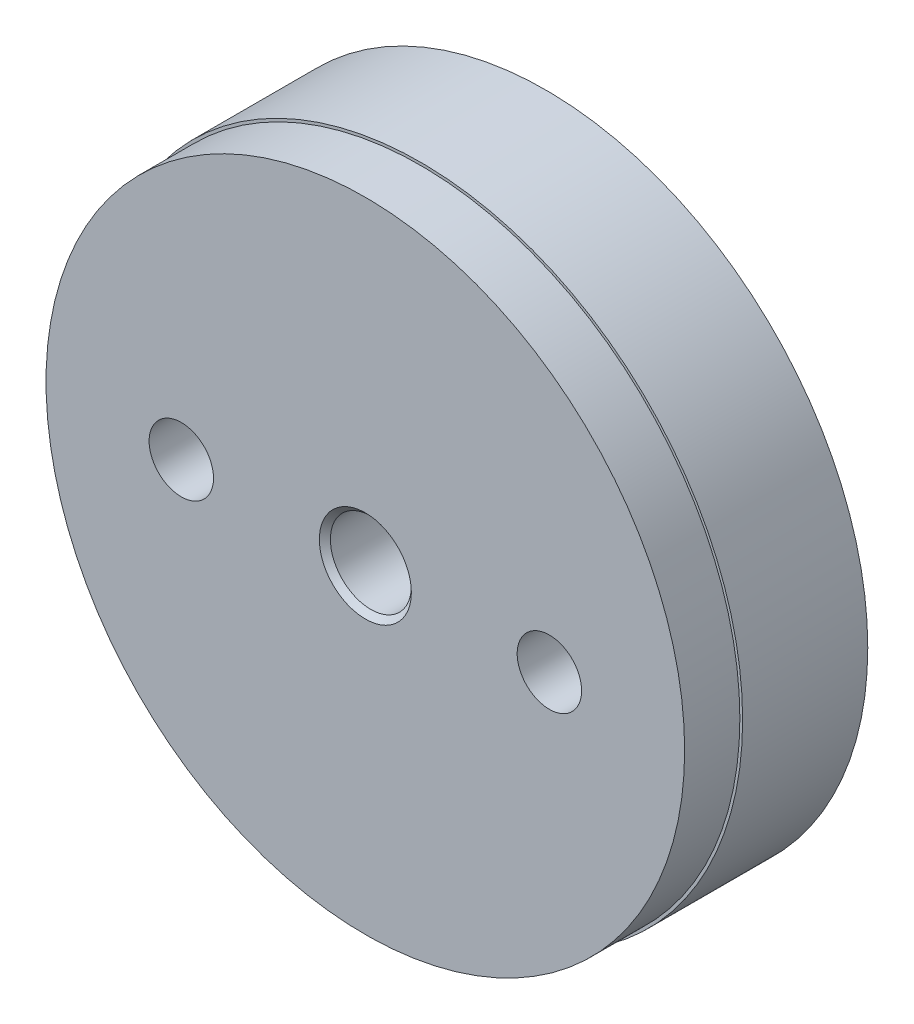
SolidWorks part; units mm, degrees
material "1.0553 (S355J0)"
ref_plane "XY Plane" through (0, 0, 0) normal (0, 0, 1) x (1, 0, 0)
ref_plane "XZ Plane" through (0, 0, 0) normal (0, 1, 0) x (1, 0, 0)
ref_plane "YZ Plane" through (0, 0, 0) normal (1, 0, 0) x (0, 0, -1)
sketch "Sketch1" plane through (0, 0, 0) normal (0, 0, 1) x (1, 0, 0)
  circle A0 centre (0, 0) radius 87.5
  dimension "D1" = 175
extrude "Boss-Extrude1" add sketch "Sketch1" along normal blind 49
sketch "Sketch2" plane through (0, 0, 49) normal (0, 0, 1) x (1, 0, 0)
  circle A0 centre (0, 0) radius 87.5 construction
  circle A1 centre (0, 0) radius 87.5
  circle A2 centre (0, 0) radius 86.75
  point P5 (0, 0)
  point P6 (0, 0)
  dimension "D1" = 173.5
extrude "Cut-Extrude1" cut sketch "Sketch2" against normal blind 15 contours A2 A1
hole_wizard "M20 Tapped Hole1" positions "Sketch3" profile "Sketch4" tap size "M20" standard "ISO" end condition through all
sketch "Sketch3" plane through (0, 0, 49) normal (0, 0, 1) x (1, 0, 0)
  line L0 (-50, 0) -> (50, 0) construction
  point P0 (-50, 0)
  point P2 (50, 0)
  dimension "D1" = 100
sketch "Sketch4" plane through (-50, 0, 49) normal (1, 0, 0) x (0, -1, 0)
  line L0 (0, 0) -> (0, 49)
  line L1 (0, 49) -> (8.75, 49)
  line L2 (8.75, 49) -> (8.75, 0)
  line L5 (8.75, 0) -> (0, 0)
  line L11 (0, -6.35) -> (0, 107.95) construction
  dimension "Thru Tap Drill Dia." = 17.5
  dimension "Thru Tap Drill Depth" = 49
cosmetic thread "Hole Thread1" parameters "D2"=20
cosmetic thread "Hole Thread2" parameters "D2"=20
hole_wizard "Ø22.0 (22) Diameter Hole1" positions "Sketch5" profile "Sketch6" hole size "Ø22.0" standard "ISO" end condition through all
sketch "Sketch5" plane through (0, 0, 49) normal (0, 0, 1) x (1, 0, 0)
  point P0 (0, 0)
sketch "Sketch6" plane through (0, 0, 49) normal (1, 0, 0) x (0, -1, 0)
  line L0 (0, 0) -> (0, 49)
  line L1 (0, 49) -> (12.5, 49)
  line L2 (11, 47.5) -> (11, 1.5)
  line L3 (11, 1.5) -> (12.5, 0)
  line L5 (12.5, 0) -> (0, 0)
  line L6 (-11, 1.5) -> (-12.5, 0) construction
  line L7 (12.5, 49) -> (11, 47.5)
  line L8 (-12.5, 49) -> (-11, 47.5) construction
  line L11 (0, -6.35) -> (0, 107.95) construction
  dimension "Thru Hole Dia." = 22
  dimension "Thru Hole Depth" = 49
  dimension "Near C'Sink Dia." = 25
  dimension "Near C'Sink Angle" = 90
  dimension "Far C'Sink Dia." = 25
  dimension "Far C'Sink Angle" = 90
